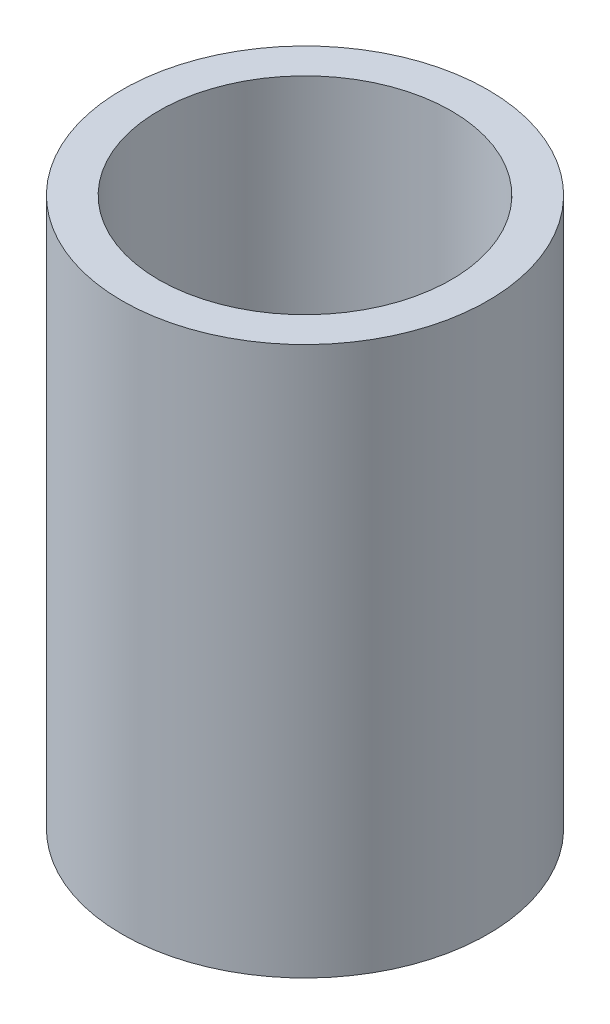
SolidWorks part; units mm, degrees
ref_plane "Спереди" through (0, 0, 0) normal (0, 0, 1) x (1, 0, 0)
ref_plane "Сверху" through (0, 0, 0) normal (0, 1, 0) x (1, 0, 0)
ref_plane "Справа" through (0, 0, 0) normal (1, 0, 0) x (0, 0, -1)
other "Configuration Table"
sketch "Эскиз1" plane through (0, 0, 0) normal (0, 1, 0) x (1, 0, 0)
  circle A0 centre (0, 0) radius 50
  circle A1 centre (0, 0) radius 40
  dimension "D1" = 100
  dimension "D2" = 80
extrude "Бобышка-Вытянуть1" add sketch "Эскиз1" along normal blind 150
